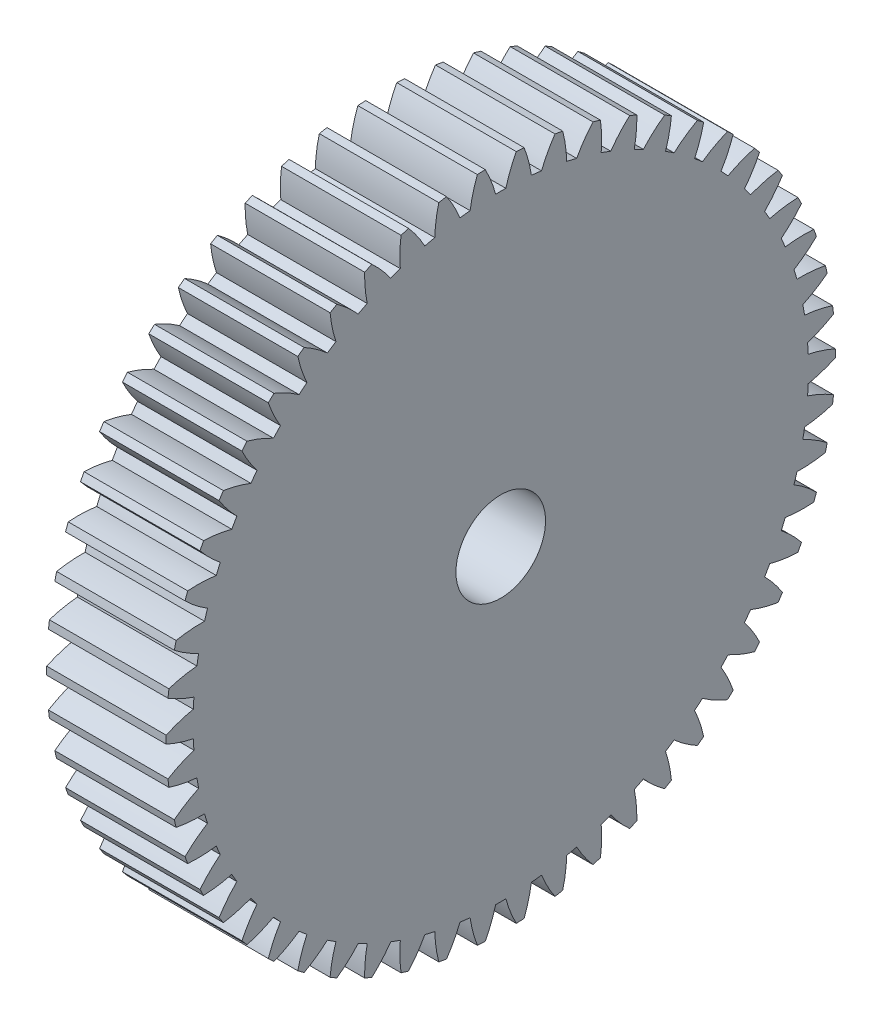
SolidWorks part; units mm, degrees
ref_plane "Plane1" through (0, 0, 0) normal (0, 0, 1) x (1, 0, 0)
ref_plane "Plane2" through (0, 0, 0) normal (0, 1, 0) x (1, 0, 0)
ref_plane "Plane3" through (0, 0, 0) normal (1, 0, 0) x (0, 0, -1)
sketch "HoldingSke" plane through (0, 0, 0) normal (0, 1, 0) x (1, 0, 0)
  line L0 (0, 0) -> (0.2939, -0.4045)
  line L1 (-15, 0) -> (100, 0) construction
  line L2 (0, 0) -> (-2.1039, 2.3779)
  line L3 (0, 0) -> (-11.863, 4.5341)
  line L4 (0, 0) -> (5.0761, 6.9867)
  line L5 (0, 0) -> (-46.8476, -17.4728)
  line L6 (0, 0) -> (-16.5793, -11.1861)
  line L7 (-2.1039, 2.3779) -> (8.6586, 51.2059)
  line L8 (-76.2, 54.61) -> (-73.9, 54.61)
  line L9 (-71.009, 38.7566) -> (-53.1078, 45.2721)
  line L10 (-76.2, 71.12) -> (104.1128, 71.12)
  line L11 (0, 0) -> (-20, 0)
  line L12 (-76.2, 101.6) -> (-76.133, 101.6)
  line L13 (24.9733, 27.94) -> (52.9518, 28.4284)
  line L14 (24.9733, 27.94) -> (24.9743, 27.94)
  line L15 (24.9733, 27.94) -> (100.4006, 29.5858)
  line L16 (-63.627, -2) -> (-12.827, -2)
  circle A0 centre (0, 0) radius 7.5
  circle A1 centre (0, 0) radius 37.5
  circle A2 centre (0, 0) radius 37.5
  circle A3 centre (0, 0) radius 7.5
  dimension "MHD" = 75
  dimension "Hub_dia" = 75
  dimension "Bore" = 15
  dimension "MBD" = 15
  dimension "Num_teeth" = 54
  dimension "Pitch" = 0.5
  dimension "Overall_len" = 50
  dimension "Show_teeth" = 54
  dimension "Thickness" = 20
  dimension "OAL" = 50.0001
  dimension "T_dim" = 2.3
  dimension "Ap" = 20
  dimension "H" = 19.05
  dimension "Pitch_radius" = 180.3128
  dimension "Width" = 20
  dimension "Backlash" = 0.067
  dimension "Addendum_fac" = 1
  dimension "Dedendum_fac" = 1.25
  dimension "Clearance_fac" = 0.25
  dimension "Dedendum_add" = 0.001
  dimension "Module" = 2
sketch "BasProSke" plane through (0, 0, 0) normal (0, 1, 0) x (1, 0, 0)
  line L0 (-10, 0) -> (60, 0) construction
  line L1 (0, 0) -> (0, 56)
  line L2 (0, 0) -> (20, 0)
  line L3 (20, 0) -> (20, 56)
  line L4 (20, 56) -> (0, 56)
  dimension "Thickness" = 20
  dimension "Diameter" = 112
revolve "Base-Revolve" add sketch "BasProSke" angle 360 about L0
sketch "TooCutSke" plane through (0, 0, 0) normal (1, 0, 0) x (0, 0, -1)
  line L1 (0, 0) -> (0, 107) construction
  line L2 (0, 0) -> (-1.6878, 53.9736) construction
  line L3 (0, 0) -> (-6.2774, 107.7782) construction
  line L4 (-1.6878, 53.9736) -> (-3.1387, 53.8891) construction
  arc A0 (0.8539, 51.4919) -> (-0.8539, 51.4919) centre (0, 0) ccw
  arc A1 (2.6145, 55.9644) -> (-2.6145, 55.9644) centre (0, 0) ccw
  circle A2 centre (0, 0) radius 54 construction
  circle A3 centre (0, 0) radius 50.7434 construction
  arc A4 (-0.8539, 51.4919) -> (-2.6145, 55.9644) centre (-21.7083, 45.8655) ccw
  arc A5 (2.6145, 55.9644) -> (0.8539, 51.4919) centre (21.7083, 45.8655) ccw
  dimension "Root_dia" = 102.998
  dimension "Overcut_dia" = 112.0508
  dimension "Pitch_dia" = 108
  dimension "Base_dia" = 101.4868
  dimension "Flank_rad" = 21.6
  dimension "Half_ang" = 3.333
  dimension "Half_CT" = 1.4533
extrude "ToothCut" cut sketch "TooCutSke" along normal through all
fillet "Breaks" [suppressed] radius 0.04
fillet "RootFillets" [suppressed] radius 0.501
pattern_circular "TeethCuts" count 54 every 6.667 about axis through (-10, 0, 0) along (1, 0, 0) of "ToothCut", "RootFillets", "Breaks"
sketch "HubNeaOneSke" plane through (0, 0, 0) normal (-1, 0, 0) x (0, 0, 1)
  circle A0 centre (0, 0) radius 37.5
  dimension "Diameter" = 75
extrude "HubNearOne" [suppressed] add sketch "HubNeaOneSke" along normal blind 30.0001
sketch "HubNeaBotSke" plane through (0, 0, 0) normal (-1, 0, 0) x (0, 0, 1)
  circle A0 centre (0, 0) radius 37.5
  dimension "Diameter" = 75
extrude "HubNearBoth" [suppressed] add sketch "HubNeaBotSke" along normal blind 15
ref_plane "FarPln" through (20, 0, 0) normal (1, 0, 0) x (0, 0, -1)
sketch "HubFarSke" plane through (20, 0, 0) normal (1, 0, 0) x (0, 0, -1)
  circle A0 centre (0, 0) radius 37.5
  dimension "Diameter" = 75
extrude "HubFar" [suppressed] add sketch "HubFarSke" along normal blind 15
sketch "BorSke" plane through (0, 0, 0) normal (1, 0, 0) x (0, 0, -1)
  circle A0 centre (0, 0) radius 7.5
  dimension "Diameter" = 15
extrude "Bore" cut sketch "BorSke" along normal mid plane 100.0001
sketch "KeySke" plane through (0, 0, 0) normal (1, 0, 0) x (0, 0, -1)
  line L0 (-2.5, 0) -> (-2.5, 9.8)
  line L1 (-2.5, 9.8) -> (2.5, 9.8)
  line L2 (2.5, 9.8) -> (2.5, 0)
  line L3 (0, 0) -> (0, 34) construction
  line L4 (-2.5, 0) -> (2.5, 0)
  dimension "Offset" = 9.8
  dimension "Width" = 5
extrude "Keyway" [suppressed] cut sketch "KeySke" along normal mid plane 100.0001
pattern_circular "Keyway2" [suppressed] count 2 every 90 about axis through (-10, 0, 0) along (1, 0, 0)
equation "' \"Module@HoldingSke\" = 6.35"
equation "' \"Num_teeth@HoldingSke\" = 12"
equation "' \"Ap@HoldingSke\" =  20"
equation "' \"Ap@HoldingSke\" = 20"
equation "' \"Width@HoldingSke\" = 0.5 * 25.4"
equation "' \"Hub_dia@HoldingSke\"= 1 * 25.4"
equation "' \"Hub_dia@HoldingSke\" = 1 * 25.4"
equation "' \"Overall_len@HoldingSke\" = 1.0 * 25.4"
equation "' \"Bore@HoldingSke\" = 0.75 * 25.4"
equation "' \"T_dim@HoldingSke\" = 0.1 * 25.4"
equation "' \"Width@KeySke\" = 0.25 * 25.4"
equation "' \"Show_teeth@HoldingSke\" = 13"
equation "' \"Backlash@HoldingSke\" = 0.009 * 25.4"
equation "' \"Addendum_fac@HoldingSke\" = 1.0"
equation "' \"Dedendum_fac@HoldingSke\" = 1.25"
equation "' \"Dedendum_add@HoldingSke\" = 0.00005 * 25.4"
equation "' \"Clearance_fac@HoldingSke\" = 0.25"
equation "\"Pitch@HoldingSke\" = 1 / \"Module@HoldingSke\""
equation "\"Overcut_dia@TooCutSke\" = (\"Num_teeth@HoldingSke\" + 2 * \"Addendum_fac@HoldingSke\") / \"Pitch@HoldingSke\" + 0.002 * 25.4"
equation "\"Pitch_dia@TooCutSke\" = \"Num_teeth@HoldingSke\" / \"Pitch@HoldingSke\""
equation "\"Base_dia@TooCutSke\" = \"Num_teeth@HoldingSke\" / \"Pitch@HoldingSke\" * cos((\"Ap@HoldingSke\"  * 3.14159265 / 180))"
equation "\"Root_dia@TooCutSke\" = (\"Num_teeth@HoldingSke\" + 2) / \"Pitch@HoldingSke\" - 2 * (\"Addendum_fac@HoldingSke\" + \"Dedendum_fac@HoldingSke\") / \"Pitch@HoldingSke\" - \"Dedendum_add@HoldingSke\" * 2"
equation "\"Half_ang@TooCutSke\" = 180 / \"Num_teeth@HoldingSke\""
equation "\"Half_CT@TooCutSke\" = \"Num_teeth@HoldingSke\" / \"Pitch@HoldingSke\" * sin((3.14159265 / 2 / \"Num_teeth@HoldingSke\")) / 2 - 7 * \"Backlash@HoldingSke\" / 4"
equation "\"Flank_rad@TooCutSke\" = \"Num_teeth@HoldingSke\" / \"Pitch@HoldingSke\" / 5"
equation "\"Radius@RootFillets\" = \"Clearance_fac@HoldingSke\" / \"Pitch@HoldingSke\" + \"Dedendum_add@HoldingSke\""
equation "\"Break_rad@Breaks\" = 0.02 / \"Pitch@HoldingSke\""
equation "\"Thickness@HoldingSke\" = \"Width@HoldingSke\""
equation "\"OAL@HoldingSke\" = \"Thickness@HoldingSke\""
equation "\"MHD@HoldingSke\" = (\"Num_teeth@HoldingSke\" + 2) / \"Pitch@HoldingSke\" - 2 * (\"Addendum_fac@HoldingSke\" + \"Dedendum_fac@HoldingSke\")  / \"Pitch@HoldingSke\" - \"Dedendum_add@HoldingSke\" * 2"
equation "\"MBD@HoldingSke\" = (\"Num_teeth@HoldingSke\" + 2) / \"Pitch@HoldingSke\" - 2 * (\"Addendum_fac@HoldingSke\" + \"Dedendum_fac@HoldingSke\")  / \"Pitch@HoldingSke\" - \"Dedendum_add@HoldingSke\" * 2 - 0.002 * 25.4"
equation "\"MHD@HoldingSke\" = ((sgn( \"MHD@HoldingSke\" - \"Hub_dia@HoldingSke\" )-1)*( \"MHD@HoldingSke\" - \"Hub_dia@HoldingSke\" ))/-2+ \"Hub_dia@HoldingSke\""
equation "\"MBD@HoldingSke\" = ((sgn( \"MBD@HoldingSke\" - \"Bore@HoldingSke\" )-1)*( \"MBD@HoldingSke\" - \"Bore@HoldingSke\" ))/-2+ \"Bore@HoldingSke\""
equation "\"OAL@HoldingSke\" = ((sgn( \"OAL@HoldingSke\" - \"Overall_len@HoldingSke\" )+1)*( \"OAL@HoldingSke\" - \"Overall_len@HoldingSke\" ))/2 + \"Overall_len@HoldingSke\" + 0.000002 * 25.4"
equation "\"Num_teeth@TeethCuts\" = int( \"Show_teeth@HoldingSke\" ) + 1"
equation "\"Num_teeth@TeethCuts\" = ((sgn( \"Num_teeth@TeethCuts\" - \"Num_teeth@HoldingSke\" )-1)*( \"Num_teeth@TeethCuts\" - \"Num_teeth@HoldingSke\" ))/-2+ \"Num_teeth@HoldingSke\""
equation "\"Num_teeth@TeethCuts\" = ((sgn( \"Num_teeth@TeethCuts\" - 2.0)+1)*( \"Num_teeth@TeethCuts\" - 2.0))/2 +2.0"
equation "\"Angle@TeethCuts\" = 360.0 / \"Num_teeth@HoldingSke\""
equation "\"Diameter@BasProSke\" = (\"Num_teeth@HoldingSke\" + 2 * \"Addendum_fac@HoldingSke\") / \"Pitch@HoldingSke\""
equation "\"Thickness@BasProSke\"  = \"Thickness@HoldingSke\""
equation "' \"Fillet_rad@BasProSke\" =  \"Thickness@HoldingSke\" * 0.05"
equation "' \"Fillet_rad@BasProSke\" = \"Thickness@HoldingSke\" * 0.05"
equation "\"MHD@HoldingSke\" = ((sgn( \"MHD@HoldingSke\" - \"Root_dia@TooCutSke\" )-1)*( \"MHD@HoldingSke\" - \"Root_dia@TooCutSke\" ))/-2+ \"Root_dia@TooCutSke\""
equation "\"Diameter@HubNeaOneSke\" = \"MHD@HoldingSke\""
equation "\"Length@HubNearOne\" = \"OAL@HoldingSke\" - \"Thickness@BasProSke\""
equation "\"Diameter@HubNeaBotSke\" = \"MHD@HoldingSke\""
equation "\"Length@HubNearBoth\" = ( \"OAL@HoldingSke\" - \"Thickness@BasProSke\" ) / 2.0"
equation "\"Thickness@FarPln\" = \"Thickness@BasProSke\""
equation "\"Diameter@HubFarSke\" = \"MHD@HoldingSke\""
equation "\"Length@HubFar\" = ( \"OAL@HoldingSke\" - \"Thickness@BasProSke\" ) / 2.0"
equation "\"Diameter@BorSke\" = \"MBD@HoldingSke\""
equation "\"D1@Bore\" = \"OAL@HoldingSke\" * 2.0"
equation "\"D1@Keyway\" = \"OAL@HoldingSke\" * 2.0"
equation "\"Offset@KeySke\" = \"T_dim@HoldingSke\" + \"MBD@HoldingSke\" / 2.0"
